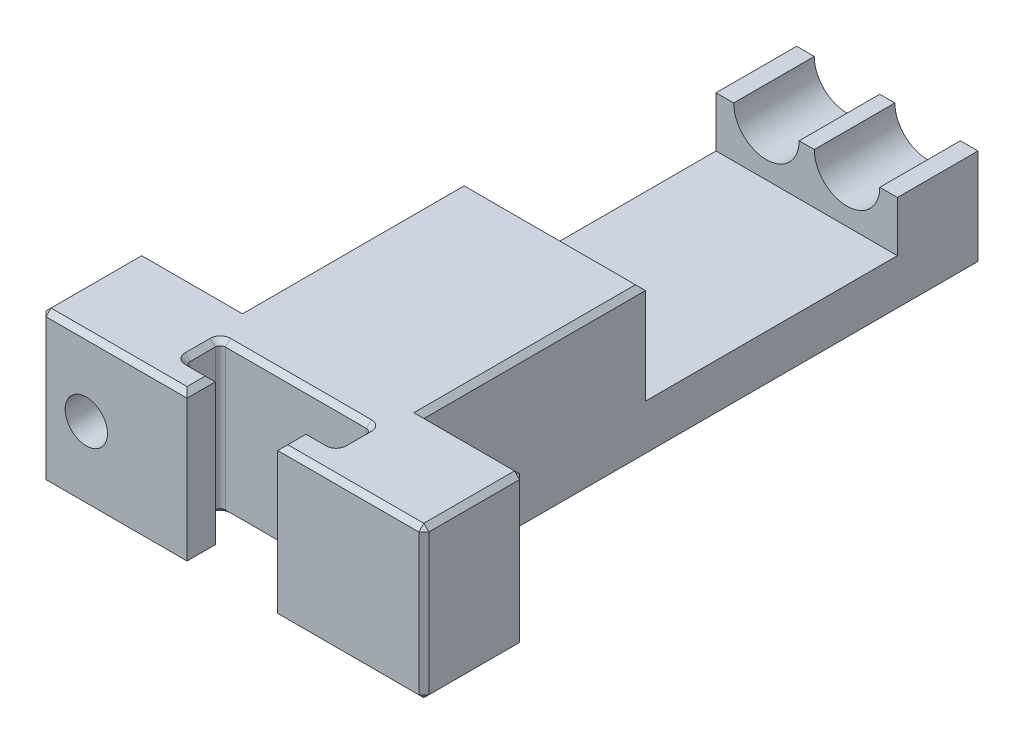
SolidWorks part; units mm, degrees
ref_plane "前视基准面" through (0, 0, 0) normal (0, 0, 1) x (1, 0, 0)
ref_plane "上视基准面" through (0, 0, 0) normal (0, 1, 0) x (1, 0, 0)
ref_plane "右视基准面" through (0, 0, 0) normal (1, 0, 0) x (0, 0, -1)
sketch "草图1" plane through (0, 0, 0) normal (0, 0, 1) x (1, 0, 0)
  line L1 (0, 0) -> (18, 0)
  line L2 (0, 0) -> (0, 10)
  line L3 (0, 10) -> (18, 10)
  line L4 (18, 0) -> (18, 10)
  dimension "D1" = 18
  dimension "D2" = 10
extrude "凸台-拉伸1" add sketch "草图1" along normal blind 65
sketch "草图2" plane through (0, 0, 0) normal (-1, 0, 0) x (0, 0, 1)
  line L0 (65, 10) -> (0, 10) construction
  line L1 (8, 10) -> (33, 10)
  line L2 (8, 10) -> (8, 5)
  line L3 (8, 5) -> (33, 5)
  line L4 (33, 10) -> (33, 5)
  line L5 (0, 10) -> (0, 0) construction
  dimension "D1" = 25
  dimension "D2" = 8
  dimension "D3" = 5
extrude "切除-拉伸1" cut sketch "草图2" against normal through all
sketch "草图3" plane through (0, 10, 0) normal (0, 1, 0) x (1, 0, 0)
  line L1 (18, -33) -> (0, -33)
  line L2 (18, -33) -> (18, -65)
  line L3 (18, -65) -> (0, -65)
  line L4 (0, -33) -> (0, -65)
extrude "凸台-拉伸2" add sketch "草图3" along normal blind 5
sketch "草图4" plane through (0, 15, 0) normal (0, 1, 0) x (1, 0, 0)
  line L0 (9, -1065) -> (9, 48935) construction
  line L1 (0, -65) -> (18, -65) construction
  line L3 (-10, -65) -> (28, -65)
  line L4 (-10, -65) -> (-10, -55)
  line L5 (-10, -55) -> (28, -55)
  line L6 (28, -65) -> (28, -55)
  point P5 (9, -65)
  dimension "D1" = 38
  dimension "D2" = 10
extrude "凸台-拉伸3" add sketch "草图4" against normal up to surface (15 mm away) up to face at (9, 0, 32.5)
hole_wizard "M5 螺纹孔1" positions "草图6" profile "草图5" tap size "M5" standard "ISO" end condition through all
sketch "草图6" plane through (0, 0, 65) normal (0, 0, 1) x (1, 0, 0)
  line L0 (-10, 15) -> (28, 15) construction
  line L3 (-10, 0) -> (-10, 15) construction
  point P0 (-5.5, 7.5)
  dimension "D1" = 7.5
  dimension "D2" = 4.5
sketch "草图5" plane through (-5.5, 7.5, 65) normal (1, 0, 0) x (0, -1, 0)
  line L0 (0, 0) -> (0, 65)
  line L1 (0, 65) -> (2.1, 65)
  line L2 (2.1, 65) -> (2.1, 0)
  line L5 (2.1, 0) -> (0, 0)
  line L11 (0, -6.35) -> (0, 107.95) construction
  dimension "通孔螺纹孔钻头直径" = 4.2
  dimension "通孔螺纹孔钻头深度" = 65
cosmetic thread "孔螺蚊线1" parameters "D2"=5
hole_wizard "Ø6.5 (6.5) 直径孔1" positions "草图8" profile "草图7" hole size "Ø6.5" standard "ISO"
sketch "草图8" plane through (0, 0, 0) normal (0, 0, -1) x (-1, 0, 0)
  line L0 (-18, 15) -> (0, 15) construction
  line L1 (-18, 15) -> (-18, 0) construction
  point P0 (-13, 10)
  dimension "D1" = 5
  dimension "D2" = 5
sketch "草图7" plane through (13, 10, 0) normal (1, 0, 0) x (0, 1, 0)
  line L0 (0, 0) -> (0, 41.9528)
  line L1 (0, 41.9528) -> (3.25, 40)
  line L2 (3.25, 40) -> (3.25, 0)
  line L5 (3.25, 0) -> (0, 0)
  line L10 (0, 41.9528) -> (-3.25, 40) construction
  line L11 (0, -6.35) -> (0, 107.95) construction
  dimension "孔直径" = 6.5
  dimension "孔深度" = 40
  dimension "导头角度" = 118
pattern_linear "阵列(线性)2" count 2 spacing 8 along (-1, 0, 0) of "Ø6.5 (6.5) 直径孔1"
sketch "草图9" plane through (0, 15, 0) normal (0, 1, 0) x (1, 0, 0)
  line L0 (9, -1033) -> (9, 48967) construction
  line L1 (18, -33) -> (0, -33) construction
  line L2 (-10, -65) -> (28, -65) construction
  line L3 (13.5, -65) -> (4.5, -65)
  line L4 (13.5, -65) -> (13.5, -62.2)
  line L6 (4.5, -65) -> (4.5, -62.2)
  line L7 (13.5, -62.2) -> (16, -62.2)
  line L8 (2, -62.2) -> (4.5, -62.2)
  line L9 (1.5, -61.7) -> (1.5, -59.2)
  line L10 (2, -58.7) -> (16, -58.7)
  line L11 (16.5, -61.7) -> (16.5, -59.2)
  arc A0 (2, -62.2) -> (1.5, -61.7) centre (2, -61.7) cw
  arc A1 (1.5, -59.2) -> (2, -58.7) centre (2, -59.2) cw
  arc A2 (16.5, -59.2) -> (16, -58.7) centre (16, -59.2) ccw
  arc A3 (16.5, -61.7) -> (16, -62.2) centre (16, -61.7) cw
  point P5 (9, -33)
  point P19 (1.5, -58.7)
  point P22 (16.5, -58.7)
  point P25 (16.5, -62.2)
  dimension "D5" = 0.5
  dimension "D1" = 2.8
  dimension "D2" = 3.5
  dimension "D3" = 9
  dimension "D4" = 15
extrude "切除-拉伸2" cut sketch "草图9" against normal through all
chamfer "倒角1" distance 0.5 angle 45 40 edges at (28, 7.5, 65) (28, 7.5, 55) (16.3536, 15, 62.0536) (16.5, 15, 60.45) (16.3536, 15, 58.8464) (9, 15, 58.7) (1.6464, 15, 58.8464) (1.5, 15, 60.45) (1.6464, 15, 62.0536) (3.25, 15, 62.2) (4.5, 15, 63.6) (-2.75, 15, 65) (14.75, 15, 62.2) (13.5, 15, 63.6) (20.75, 15, 65) (28, 0, 60) (28, 15, 60) (23, 15, 55) (23, 0, 55) (18, 15, 44) (9, 15, 33) (0, 15, 44) (-5, 0, 55) (-5, 15, 55) (-10, 7.5, 55) (-10, 0, 60) (-10, 15, 60) (-10, 7.5, 65) (18, 0, 27.5) (0, 0, 27.5) (-2.75, 0, 65) (3.25, 0, 62.2) (1.6464, 0, 62.0536) (1.5, 0, 60.45) (1.6464, 0, 58.8464) (16.3536, 0, 58.8464) (16.5, 0, 60.45) (16.3536, 0, 62.0536) (14.75, 0, 62.2) (20.75, 0, 65)
sketch "草图10" plane through (0, 0, 0) normal (0, -1, 0) x (1, 0, 0)
  line L0 (9, -941.8) -> (9, 49058.2) construction
  line L1 (16, 58.2) -> (2, 58.2) construction
  line L3 (3, 72.1247) -> (15, 72.1247)
  line L4 (3, 72.1247) -> (3, -5.4927)
  line L5 (3, -5.4927) -> (15, -5.4927)
  line L6 (15, 72.1247) -> (15, -5.4927)
  point P5 (9, 58.2)
  dimension "D1" = 12
extrude "切除-拉伸3" cut sketch "草图10" against normal blind 0.5
